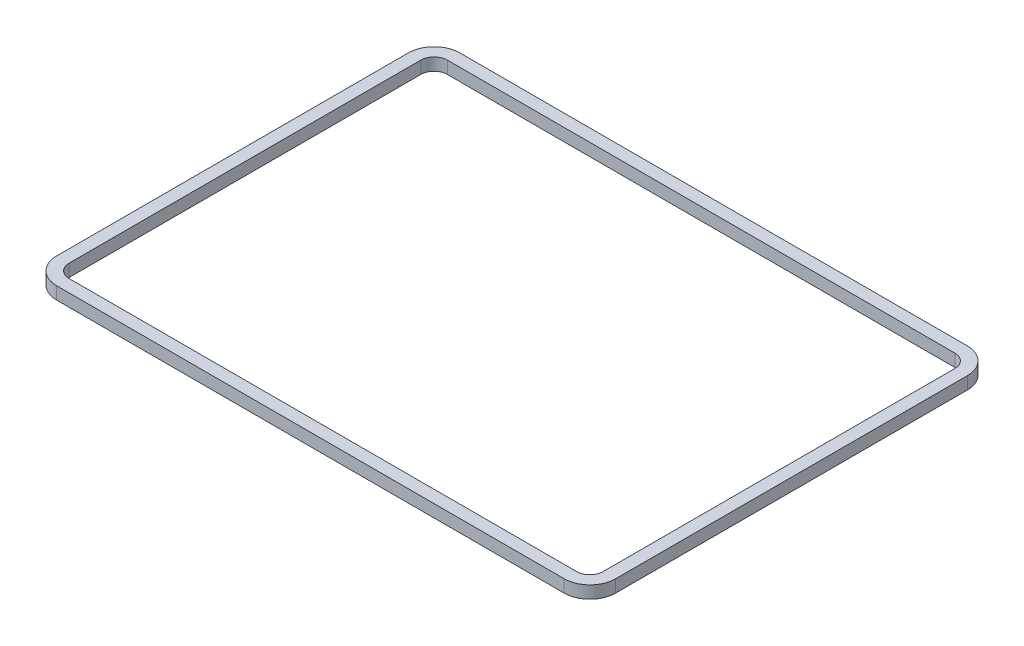
SolidWorks part; units mm, degrees
material "Rubber"
ref_plane "Front" through (0, 0, 0) normal (0, 0, 1) x (1, 0, 0)
ref_plane "Top" through (0, 0, 0) normal (0, 1, 0) x (1, 0, 0)
ref_plane "Right" through (0, 0, 0) normal (1, 0, 0) x (0, 0, -1)
sketch "Sketch1" plane through (0, 0, 0) normal (0, 1, 0) x (1, 0, 0)
  line L0 (-108.839, -77.089) -> (108.839, 77.089) construction
  line L1 (-108.839, 77.089) -> (108.839, 77.089)
  line L2 (-108.839, 77.089) -> (-108.839, -77.089)
  line L3 (-108.839, -77.089) -> (108.839, -77.089)
  line L4 (108.839, 77.089) -> (108.839, -77.089)
  line L5 (-113.919, 82.169) -> (113.919, 82.169)
  line L6 (113.919, 82.169) -> (113.919, -82.169)
  line L7 (-113.919, -82.169) -> (113.919, -82.169)
  line L8 (-113.919, 82.169) -> (-113.919, -82.169)
  point P4 (0, 0)
  dimension "D1" = 217.678
  dimension "D2" = 154.178
  dimension "D3" = 5.08
extrude "Extrude1" add sketch "Sketch1" along normal blind 5.08
fillet "Fillet1" radius 5.4102 4 edges at (108.839, 2.54, -77.089) (108.839, 2.54, 77.089) (-108.839, 2.54, 77.089) (-108.839, 2.54, -77.089)
fillet "Fillet2" radius 10.4902 4 edges at (-113.919, 2.54, -82.169) (-113.919, 2.54, 82.169) (113.919, 2.54, 82.169) (113.919, 2.54, -82.169)
